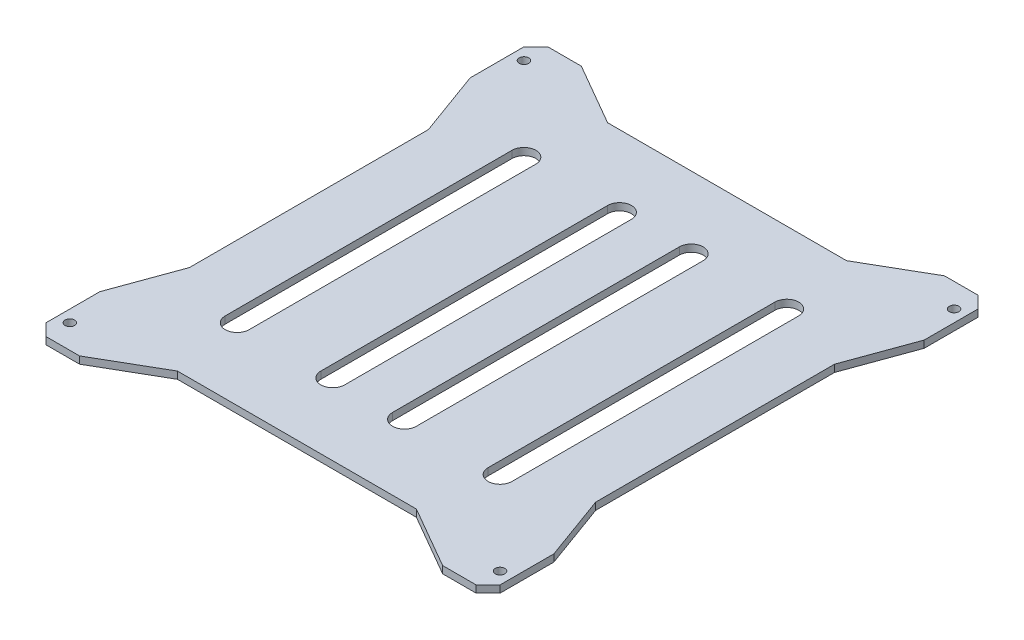
SolidWorks part; units mm, degrees
ref_plane "前视基准面" through (0, 0, 0) normal (0, 0, 1) x (1, 0, 0)
ref_plane "上视基准面" through (0, 0, 0) normal (0, 1, 0) x (1, 0, 0)
ref_plane "右视基准面" through (0, 0, 0) normal (1, 0, 0) x (0, 0, -1)
sketch "草图1" plane through (0, 0, 0) normal (0, 1, 0) x (1, 0, 0)
  line L1 (-98, 164) -> (98, 164)
  line L2 (-98, 164) -> (-98, -164)
  line L3 (-98, -164) -> (98, -164)
  line L4 (98, 164) -> (98, -164)
  point P4 (0, 164)
  point P6 (98, 0)
  dimension "D1" = 196
  dimension "D2" = 328
sketch "草图2" plane through (0, 0, 0) normal (0, 1, 0) x (1, 0, 0)
  line L0 (-95, 0) -> (0, 0) construction
  line L1 (-95, 105) -> (95, 105)
  line L2 (-95, 105) -> (-95, -105)
  line L3 (-95, -105) -> (95, -105)
  line L4 (95, 105) -> (95, -105)
  line L5 (0, 0) -> (0, 105) construction
  circle A0 centre (-90, 95) radius 2
  circle A1 centre (90, 95) radius 2
  circle A2 centre (90, -95) radius 2
  circle A3 centre (-90, -95) radius 2
  point P4 (95, 0)
  point P6 (0, 105)
  dimension "D5" = 4
  dimension "D1" = 210
  dimension "D2" = 190
  dimension "D3" = 190
  dimension "D4" = 180
extrude "凸台-拉伸1" add sketch "草图2" along normal blind 3
sketch "草图3" plane through (0, 0, 0) normal (0, 1, 0) x (1, 0, 0)
  line L0 (-95, 0) -> (95, 0) construction
  line L1 (-95, 105) -> (-95, -105) construction
  line L2 (95, -105) -> (95, 105) construction
  line L3 (0, 105) -> (0, -105) construction
  line L4 (95, 105) -> (-95, 105) construction
  line L5 (-95, -105) -> (95, -105) construction
  line L6 (-75.9808, 105) -> (-50, 90)
  line L7 (-50, 90) -> (50, 90)
  line L8 (-95, 77.4748) -> (-85, 50)
  line L9 (-85, 50) -> (-85, -50)
  line L10 (-55, 60) -> (-55, -60) construction
  line L11 (-50, 60) -> (-50, -60)
  line L12 (-60, 60) -> (-60, -60)
  line L13 (-15, 60) -> (-15, -60) construction
  line L14 (-10, 60) -> (-10, -60)
  line L15 (-20, 60) -> (-20, -60)
  line L16 (15, 60) -> (15, -60) construction
  line L17 (10, 60) -> (10, -60)
  line L18 (20, 60) -> (20, -60)
  line L19 (55, 60) -> (55, -60) construction
  line L20 (50, 60) -> (50, -60)
  line L21 (60, 60) -> (60, -60)
  line L22 (85, 50) -> (85, -50)
  line L23 (95, 77.4748) -> (85, 50)
  line L24 (75.9808, 105) -> (50, 90)
  line L25 (95, -77.4748) -> (85, -50)
  line L26 (75.9808, -105) -> (50, -90)
  line L27 (-50, -90) -> (50, -90)
  line L28 (-75.9808, -105) -> (-50, -90)
  line L29 (-95, -77.4748) -> (-85, -50)
  line L30 (-95, 77.4748) -> (-95, -77.4748)
  line L31 (95, 77.4748) -> (95, -77.4748)
  line L32 (75.9808, 105) -> (-75.9808, 105)
  line L33 (-75.9808, -105) -> (75.9808, -105)
  arc A0 (-50, 60) -> (-60, 60) centre (-55, 60) ccw
  arc A1 (-60, -60) -> (-50, -60) centre (-55, -60) ccw
  arc A2 (-10, 60) -> (-20, 60) centre (-15, 60) ccw
  arc A3 (-20, -60) -> (-10, -60) centre (-15, -60) ccw
  arc A4 (10, 60) -> (20, 60) centre (15, 60) cw
  arc A5 (20, -60) -> (10, -60) centre (15, -60) cw
  arc A6 (50, 60) -> (60, 60) centre (55, 60) cw
  arc A7 (60, -60) -> (50, -60) centre (55, -60) cw
  point P20 (-55, 0)
  point P25 (-15, 0)
  point P36 (15, 0)
  point P43 (55, 0)
  point P52 (0, 90)
  point P55 (85, 0)
  point P59 (0, -90)
  point P61 (-85, 0)
  dimension "D8" = 5
  dimension "D1" = 10
  dimension "D2" = 50
  dimension "D3" = 20
  dimension "D4" = 15
  dimension "D5" = 30
  dimension "D6" = 50
  dimension "D7" = 120
  dimension "D9" = 15
  dimension "D10" = 40
extrude "切除-拉伸1" cut sketch "草图3" along normal through all
chamfer "倒角1" distance 5 angle 45 4 edges at (-95, 1.5, 105) (95, 1.5, 105) (95, 1.5, -105) (-95, 1.5, -105)
